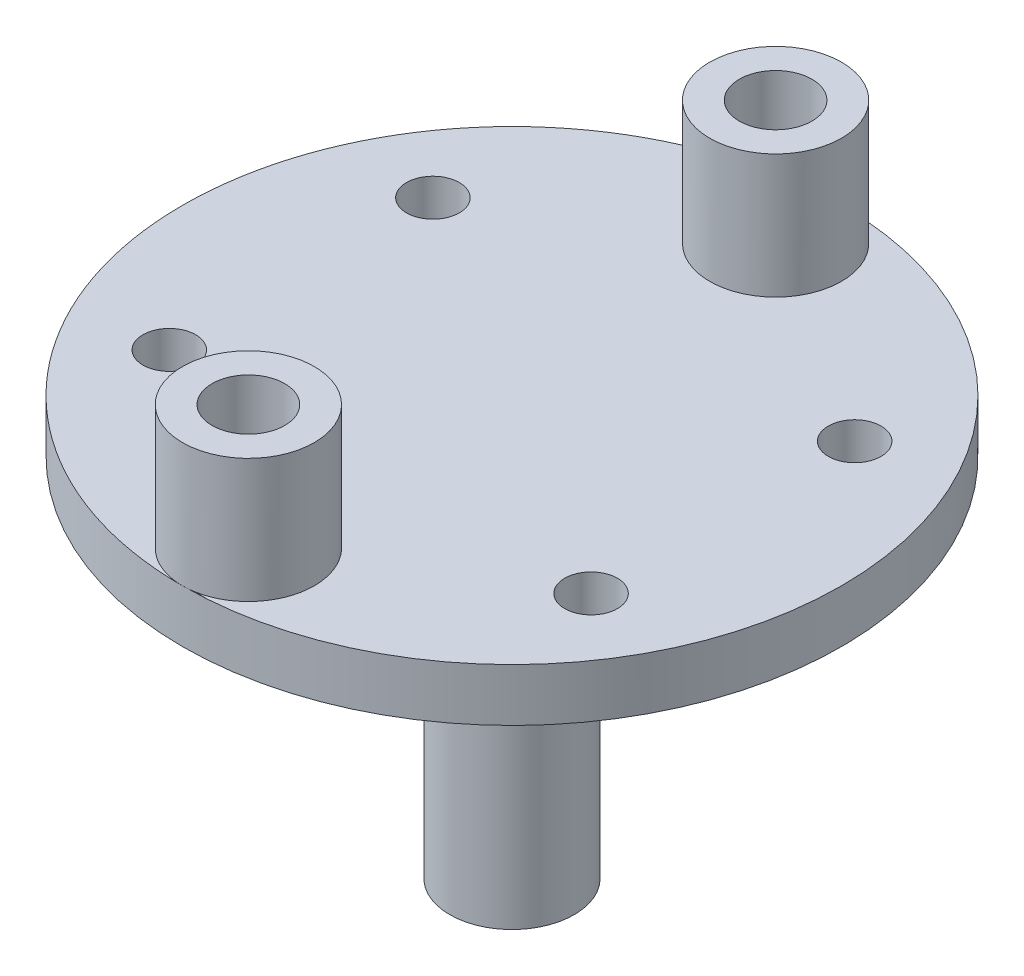
SolidWorks part; units mm, degrees
material "PLA"
ref_plane "Front Plane" through (0, 0, 0) normal (0, 0, 1) x (1, 0, 0)
ref_plane "Top Plane" through (0, 0, 0) normal (0, 1, 0) x (1, 0, 0)
ref_plane "Right Plane" through (0, 0, 0) normal (1, 0, 0) x (0, 0, -1)
sketch "Sketch1" plane through (0, 0, 0) normal (0, 1, 0) x (1, 0, 0)
  line L0 (0, 8.89) -> (25.4, 8.89) construction
  line L5 (0, 0) -> (25.4, 0)
  line L6 (0, 0) -> (0, 17.78)
  line L7 (0, 17.78) -> (25.4, 17.78)
  line L8 (25.4, 0) -> (25.4, 17.78)
  line L9 (12.7, 17.78) -> (12.7, 0) construction
  circle A2 centre (2.54, 15.24) radius 1.27
  circle A3 centre (22.86, 15.24) radius 1.27
  circle A4 centre (22.86, 2.54) radius 1.27
  circle A5 centre (2.54, 2.54) radius 1.27
  circle A6 centre (12.7, 8.89) radius 15.875
  circle A7 centre (12.7, 21.59) radius 1.75
  circle A8 centre (12.7, -3.81) radius 1.75
  dimension "D3" = 2.54
  dimension "D6" = 31.75
  dimension "D7" = 3.5
  dimension "D1" = 17.78
  dimension "D2" = 25.4
  dimension "D4" = 20.32
  dimension "D5" = 12.7
  dimension "D8" = 12.7
extrude "Boss-Extrude1" add sketch "Sketch1" along normal blind 2.54 contours L5 L8 L7 L6 A3 A2 A4 A5 | A6 L8 L5 L6 L7 A7 A8
sketch "Sketch2" plane through (0, 2.54, 0) normal (0, 1, 0) x (1, 0, 0)
  circle A0 centre (12.7, -3.81) radius 1.75 construction
  circle A1 centre (12.7, 8.89) radius 15.875
  circle A2 centre (12.7, 8.89) radius 15.875
  circle A3 centre (12.7, 21.59) radius 1.75 construction
  circle A4 centre (12.7, -3.81) radius 1.75
  circle A5 centre (12.7, 21.59) radius 1.75
  circle A6 centre (12.7, 21.59) radius 3.175
  circle A7 centre (12.7, -3.81) radius 3.175
  circle M8 centre (12.7, 21.59) radius 1.75
  circle M9 centre (12.7, -3.81) radius 1.75
  dimension "D1" = 0
extrude "Boss-Extrude2" add sketch "Sketch2" along normal blind 5.975 contours A6 M8 | A7 M9
sketch "Sketch3" plane through (0, 0, 0) normal (0, -1, 0) x (1, 0, 0)
  circle A0 centre (12.7, -8.89) radius 3
  circle A1 centre (12.7, -8.89) radius 15.875
  circle A2 centre (12.7, -8.89) radius 15.875
  dimension "D2" = 6
  dimension "D1" = 0
extrude "Boss-Extrude3" add sketch "Sketch3" along normal blind 17.62 contours A0
